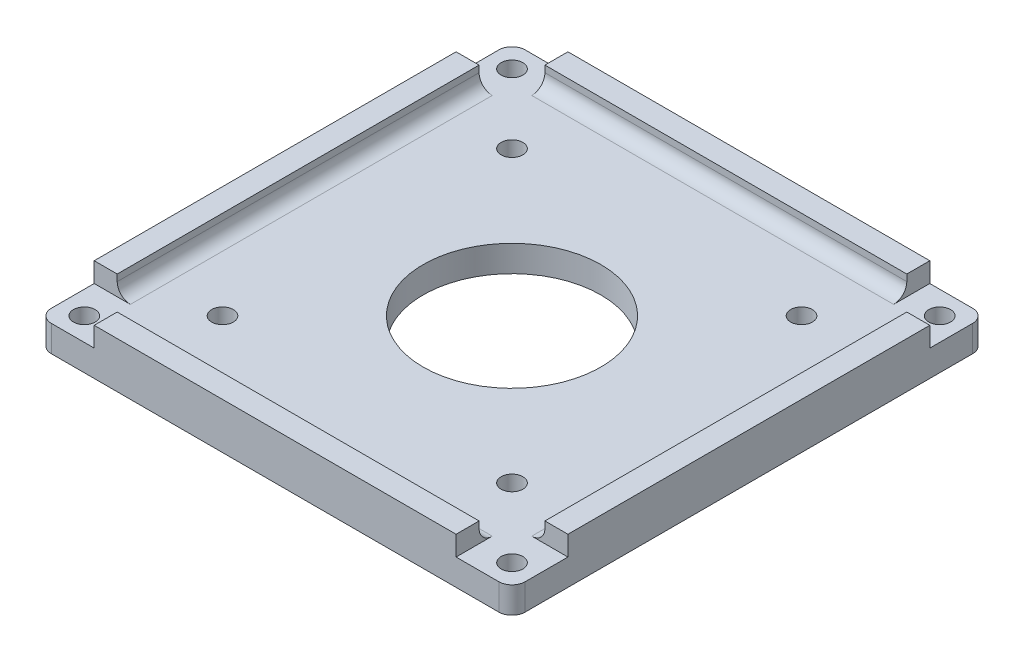
SolidWorks part; units mm, degrees
ref_plane "前视基准面" through (0, 0, 0) normal (0, 0, 1) x (1, 0, 0)
ref_plane "上视基准面" through (0, 0, 0) normal (0, 1, 0) x (1, 0, 0)
ref_plane "右视基准面" through (0, 0, 0) normal (1, 0, 0) x (0, 0, -1)
other "Configuration Table"
sketch "草图1" plane through (0, 0, 0) normal (0, 1, 0) x (1, 0, 0)
  line L1 (-36, -36) -> (36, -36)
  line L2 (-36, -36) -> (-36, 36)
  line L3 (-36, 36) -> (36, 36)
  line L4 (36, -36) -> (36, 36)
  line L5 (-36, -36) -> (36, 36) construction
  line L6 (-36, 36) -> (36, -36) construction
  circle A0 centre (0, 0) radius 13.5
  point P0 (0, 0)
  dimension "D3" = 27
  dimension "D2" = 72
extrude "凸台-拉伸1" add sketch "草图1" along normal blind 4
sketch "草图2" plane through (0, 0, 0) normal (0, 1, 0) x (1, 0, 0)
  line L1 (-22, -22) -> (22, -22) construction
  line L2 (-22, -22) -> (-22, 22) construction
  line L3 (-22, 22) -> (22, 22) construction
  line L4 (22, -22) -> (22, 22) construction
  line L5 (-22, -22) -> (22, 22) construction
  line L6 (-22, 22) -> (22, -22) construction
  line L7 (-32.5, -32.5) -> (32.5, -32.5) construction
  line L8 (-32.5, -32.5) -> (-32.5, 32.5) construction
  line L9 (-32.5, 32.5) -> (32.5, 32.5) construction
  line L10 (32.5, -32.5) -> (32.5, 32.5) construction
  line L11 (-32.5, -32.5) -> (32.5, 32.5) construction
  line L12 (-32.5, 32.5) -> (32.5, -32.5) construction
  circle A0 centre (-22, 22) radius 1.65
  circle A1 centre (22, 22) radius 1.65
  circle A2 centre (22, -22) radius 1.65
  circle A3 centre (-22, -22) radius 1.65
  circle A4 centre (-32.5, 32.5) radius 1.65
  circle A5 centre (32.5, 32.5) radius 1.65
  circle A6 centre (32.5, -32.5) radius 1.65
  circle A7 centre (-32.5, -32.5) radius 1.65
  point P0 (0, 0)
  point P10 (0, 0)
  dimension "D2" = 3.3
  dimension "D3" = 3.3
  dimension "D1" = 44
  dimension "D4" = 65
extrude "切除-拉伸5" cut sketch "草图2" along normal blind 4
fillet "圆角1" radius 2 4 edges at (36, 2, -36) (36, 2, 36) (-36, 2, 36) (-36, 2, -36)
sketch "草图3" plane through (0, 4, 0) normal (0, 1, 0) x (1, 0, 0)
  line L0 (-36, 34) -> (-36, -34) construction
  line L1 (-36, 27.5) -> (-32.5, 27.5)
  line L2 (-36, 27.5) -> (-36, -27.5)
  line L3 (-36, -27.5) -> (-32.5, -27.5)
  line L4 (-32.5, 27.5) -> (-32.5, -27.5)
  line L5 (34, 36) -> (-34, 36) construction
  line L6 (-27.5, 36) -> (27.5, 36)
  line L7 (-27.5, 36) -> (-27.5, 32.5)
  line L8 (-27.5, 32.5) -> (27.5, 32.5)
  line L9 (27.5, 36) -> (27.5, 32.5)
  line L10 (36, -34) -> (36, 34) construction
  line L11 (36, 27.5) -> (32.5, 27.5)
  line L12 (36, 27.5) -> (36, -27.5)
  line L13 (36, -27.5) -> (32.5, -27.5)
  line L14 (32.5, 27.5) -> (32.5, -27.5)
  line L15 (-34, -36) -> (34, -36) construction
  line L16 (-27.5, -36) -> (27.5, -36)
  line L17 (-27.5, -36) -> (-27.5, -32.5)
  line L18 (-27.5, -32.5) -> (27.5, -32.5)
  line L19 (27.5, -36) -> (27.5, -32.5)
  line L20 (0, 36) -> (0, -36) construction
  line L21 (-36, 0) -> (36, 0) construction
  dimension "D1" = 55
  dimension "D2" = 3.5
  dimension "D3" = 55
extrude "凸台-拉伸2" add sketch "草图3" along normal blind 3
fillet "圆角2" radius 2 4 edges at (32.5, 4, 0) (0, 4, -32.5) (-32.5, 4, 0) (0, 4, 32.5)
